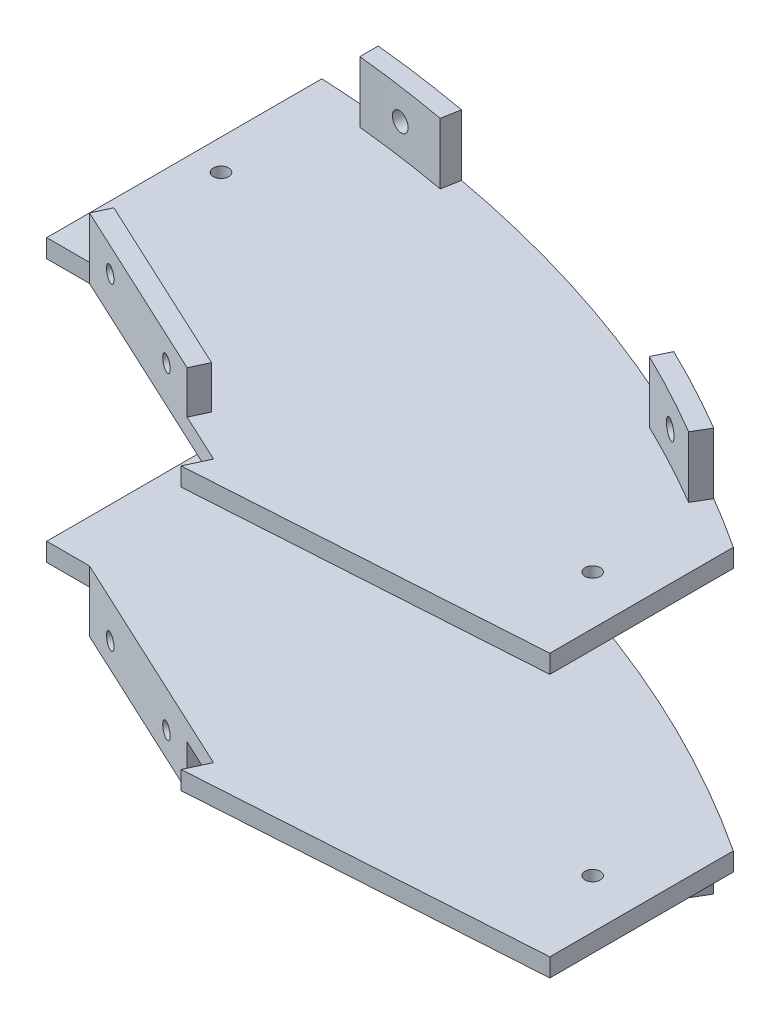
SolidWorks part; units mm, degrees
ref_plane "Front Plane" through (0, 0, 0) normal (0, 0, 1) x (1, 0, 0)
ref_plane "Top Plane" through (0, 0, 0) normal (0, 1, 0) x (1, 0, 0)
ref_plane "Right Plane" through (0, 0, 0) normal (1, 0, 0) x (0, 0, -1)
sketch "Sketch1" plane through (0, 0, 0) normal (0, 1, 0) x (1, 0, 0)
  line L0 (0, 45) -> (0, 0)
  line L1 (0, 0) -> (7, 0)
  line L2 (7, 0) -> (45.0015, -17.7204)
  line L3 (45.0015, -17.7204) -> (43.311, -21.3456)
  line L4 (43.311, -21.3456) -> (100.0015, -21.3456) construction
  line L5 (100.0015, -21.3456) -> (100.0015, -17.7204) construction
  line L6 (45.0015, -17.7204) -> (100.0015, -17.7204) construction
  line L7 (100.0015, -17.7204) -> (100.0015, 12.2796)
  line L8 (43.311, -21.3456) -> (100.0015, -17.7204)
  arc A0 (0, 45) -> (100.0015, 12.2796) centre (-10.0041, -154.7496) cw
  dimension "D5" = 4
  dimension "D7" = 30
  dimension "D8" = 200
  dimension "D1" = 45
  dimension "D2" = 7
  dimension "D3" = 41.93
  dimension "D4" = 155
  dimension "D6" = 55
extrude "Boss-Extrude1" add sketch "Sketch1" along normal blind 3
sketch "Sketch2" plane through (1.2502, 0, -2.6812) normal (-0.4226, 0, 0.9063) x (0.9063, 0, 0.4226)
  line L0 (6.3442, 0) -> (6.3442, 10)
  line L1 (6.3442, 10) -> (39.3442, 10)
  line L2 (39.3442, 10) -> (39.3442, 0)
  line L3 (39.3442, 0) -> (6.3442, 0)
  line L4 (13.3442, 6) -> (13.3442, 3) construction
  line L5 (6.3442, 3) -> (48.2742, 3) construction
  circle A0 centre (13.3442, 6) radius 1.25
  circle A1 centre (32.3442, 6) radius 1.25
  dimension "D1" = 2.5
  dimension "D5" = 19
  dimension "D6" = 7
  dimension "D2" = 3
  dimension "D3" = 4
  dimension "D4" = 7
extrude "Boss-Extrude2" add sketch "Sketch2" against normal blind 3
sketch "Sketch3" plane through (0, 0, 0) normal (0, -1, 0) x (1, 0, 0)
  line L0 (0, -45) -> (0, -23.5) construction
  line L1 (0, -45) -> (0, 0) construction
  line L2 (0, -23.5) -> (5, -23.5) construction
  line L3 (92.0015, 2.7204) -> (100.0015, 2.7204) construction
  line L4 (100.0015, 17.7204) -> (100.0015, -12.2796) construction
  circle A0 centre (5, -23.5) radius 1.25
  circle A1 centre (92.0015, 2.7204) radius 1.25
  dimension "D1" = 21.5
  dimension "D3" = 2.5
  dimension "D4" = 8
  dimension "D2" = 5
extrude "Cut-Extrude1" cut sketch "Sketch3" against normal through all
sketch "Sketch6" plane through (0, 3, 0) normal (0, 1, 0) x (1, 0, 0)
  line L0 (0, 45) -> (0, 0) construction
  line L1 (100.0015, -17.7204) -> (100.0015, 12.2796) construction
  line L2 (9.9719, 44.2503) -> (9.9719, 41.2388)
  line L3 (25.8152, 42.0167) -> (25.2786, 39.0689)
  line L4 (91.5151, 17.5694) -> (89.9943, 14.9879)
  line L5 (77.4158, 25.133) -> (76.1061, 22.4382)
  arc A0 (0, 45) -> (100.0015, 12.2796) centre (-10.0041, -154.7496) cw
  arc A1 (100.0015, 12.2796) -> (0, 45) centre (-10.0041, -154.7496) ccw construction
  arc A2 (0, 42) -> (100.0015, 8.6801) centre (-10.0041, -154.7496) cw
  arc M11 (100.0015, 12.2796) -> (0, 45) centre (-10.0041, -154.7496) ccw
  dimension "D1" = 3
  dimension "D2" = 10
  dimension "D3" = 16
  dimension "D4" = 10
  dimension "D5" = 16
extrude "Boss-Extrude3" add sketch "Sketch6" along normal blind 10 contours L2 A2 L3 M11 | L5 A2 L4 M11
sketch "Sketch7" plane through (0, 13, 0) normal (0, 1, 0) x (1, 0, 0)
  line L0 (17.9159, 43.292) -> (-10.0041, -154.7496) construction
  line L1 (-10.0041, -154.7496) -> (84.5411, 21.4922) construction
  arc A0 (25.8152, 42.0167) -> (9.9719, 44.2503) centre (-10.0041, -154.7496) ccw construction
  arc A1 (91.5151, 17.5694) -> (77.4158, 25.133) centre (-10.0041, -154.7496) ccw construction
ref_plane "Plane1" through (17.9159, 13, -43.292) normal (0.1396, 0, -0.9902) x (-0.9902, 0, -0.1396)
sketch "Sketch8" plane through (17.9159, 13, -43.292) normal (0.1396, 0, -0.9902) x (-0.9902, 0, -0.1396)
  line L0 (-8, 0) -> (8, -10) construction
  circle A0 centre (0, -5) radius 1.5
  dimension "D1" = 3
extrude "Cut-Extrude2" cut sketch "Sketch8" against normal up to surface (3.0019 mm away)
ref_plane "Plane2" through (84.5411, 13, -21.4922) normal (0.4727, 0, -0.8812) x (-0.8812, 0, -0.4727)
sketch "Sketch9" plane through (84.5411, 13, -21.4922) normal (0.4727, 0, -0.8812) x (-0.8812, 0, -0.4727)
  line L0 (-8, 0) -> (8, -10) construction
  circle A0 centre (0, -5) radius 1.5
  dimension "D1" = 3
extrude "Cut-Extrude3" cut sketch "Sketch9" against normal up to surface (3.0019 mm away)
ref_plane "Plane3" through (0, -20, 0) normal (0, -1, 0) x (-1, 0, 0)
mirror "Mirror1" about plane through (0, -20, 0) normal (0, -1, 0) of bodies 106
